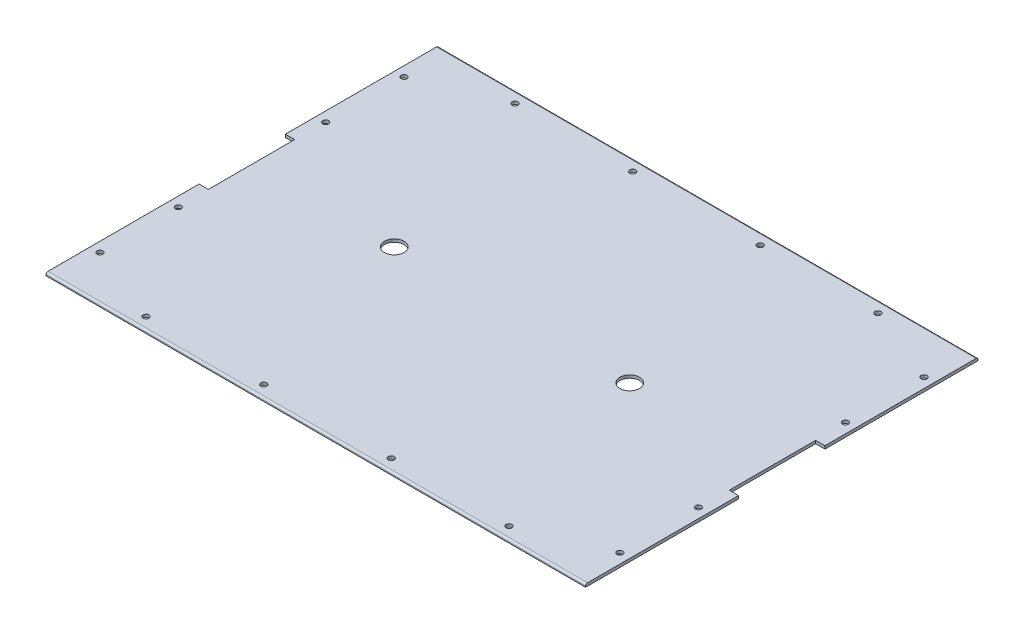
SolidWorks part; units mm, degrees
ref_plane "前视基准面" through (0, 0, 0) normal (0, 0, 1) x (1, 0, 0)
ref_plane "上视基准面" through (0, 0, 0) normal (0, 1, 0) x (1, 0, 0)
ref_plane "右视基准面" through (0, 0, 0) normal (1, 0, 0) x (0, 0, -1)
sketch "草图1" plane through (0, 0, 0) normal (0, 1, 0) x (1, 0, 0)
  line L0 (0, 0) -> (-343.9318, 0) construction
  line L1 (-275, -200) -> (275, -200)
  line L2 (-275, -200) -> (-275, -44)
  line L3 (-275, 200) -> (275, 200)
  line L4 (275, -200) -> (275, -44)
  line L5 (-275, -200) -> (275, 200) construction
  line L6 (-275, 200) -> (275, -200) construction
  line L7 (0, 0) -> (0, 279.2477) construction
  line L8 (275, -200) -> (275, -44)
  line L9 (-275, 44) -> (-265.5, 44)
  line L10 (-265.5, 44) -> (-265.5, -44)
  line L11 (-265.5, -44) -> (-275, -44)
  line L12 (-275, 44) -> (-275, 200)
  line L13 (265.5, -44) -> (275, -44)
  line L14 (265.5, 44) -> (265.5, -44)
  line L15 (275, 44) -> (265.5, 44)
  line L16 (275, 44) -> (275, 200)
  line L17 (275, 44) -> (275, 200)
  circle A0 centre (-265, -75) radius 3
  circle A1 centre (-265, -155) radius 3
  circle A2 centre (-185, -188) radius 3
  circle A3 centre (-65, -188) radius 3
  circle A4 centre (-65, 188) radius 3
  circle A5 centre (-185, 188) radius 3
  circle A6 centre (-265, 155) radius 3
  circle A7 centre (-265, 75) radius 3
  circle A8 centre (-265, -75) radius 3
  circle A9 centre (-265, -155) radius 3
  circle A10 centre (-185, -188) radius 3
  circle A11 centre (-65, -188) radius 3
  circle A12 centre (-65, 188) radius 3
  circle A13 centre (-185, 188) radius 3
  circle A14 centre (-265, 155) radius 3
  circle A15 centre (-265, 75) radius 3
  circle A16 centre (265, 75) radius 3
  circle A17 centre (265, 155) radius 3
  circle A18 centre (185, 188) radius 3
  circle A19 centre (65, 188) radius 3
  circle A20 centre (65, -188) radius 3
  circle A21 centre (185, -188) radius 3
  circle A22 centre (265, -155) radius 3
  circle A23 centre (265, -75) radius 3
  circle A24 centre (265, 75) radius 3
  circle A25 centre (265, 155) radius 3
  circle A26 centre (185, 188) radius 3
  circle A27 centre (65, 188) radius 3
  circle A28 centre (65, -188) radius 3
  circle A29 centre (185, -188) radius 3
  circle A30 centre (265, -155) radius 3
  circle A31 centre (265, -75) radius 3
  circle A32 centre (-120, 0) radius 10
  circle A33 centre (120, 0) radius 10
  point P0 (0, 0)
  dimension "D3" = 6
  dimension "D4" = 6
  dimension "D5" = 6
  dimension "D6" = 6
  dimension "D15" = 20
  dimension "D16" = 20
  dimension "D1" = 550
  dimension "D2" = 400
  dimension "D7" = 80
  dimension "D8" = 120
  dimension "D9" = 10
  dimension "D10" = 12
  dimension "D11" = 80
  dimension "D12" = 33
  dimension "D13" = 9.5
  dimension "D14" = 88
  dimension "D17" = 120
extrude "凸台-拉伸1" add sketch "草图1" along normal blind 3 contours L1 L4 L3 L2 A22 A20 A19 A18 A17 A16 A6 A4 A3 A2 A1 A0 A5 A7 A21 A23
sketch "草图2" plane through (0, 3, 0) normal (0, 1, 0) x (1, 0, 0)
  line L0 (0, 0) -> (0, 200) construction
  line L1 (-275, 200) -> (275, 200) construction
  line L2 (-45, 200) -> (-45, -200)
  line L3 (-275, -200) -> (275, -200) construction
  line L4 (45, 200) -> (45, -200)
  dimension "D1" = 45
fillet "圆角1" radius 2 1 edges at (0, 3, 200)
fillet "圆角2" radius 2 1 edges at (0, 3, -200)
